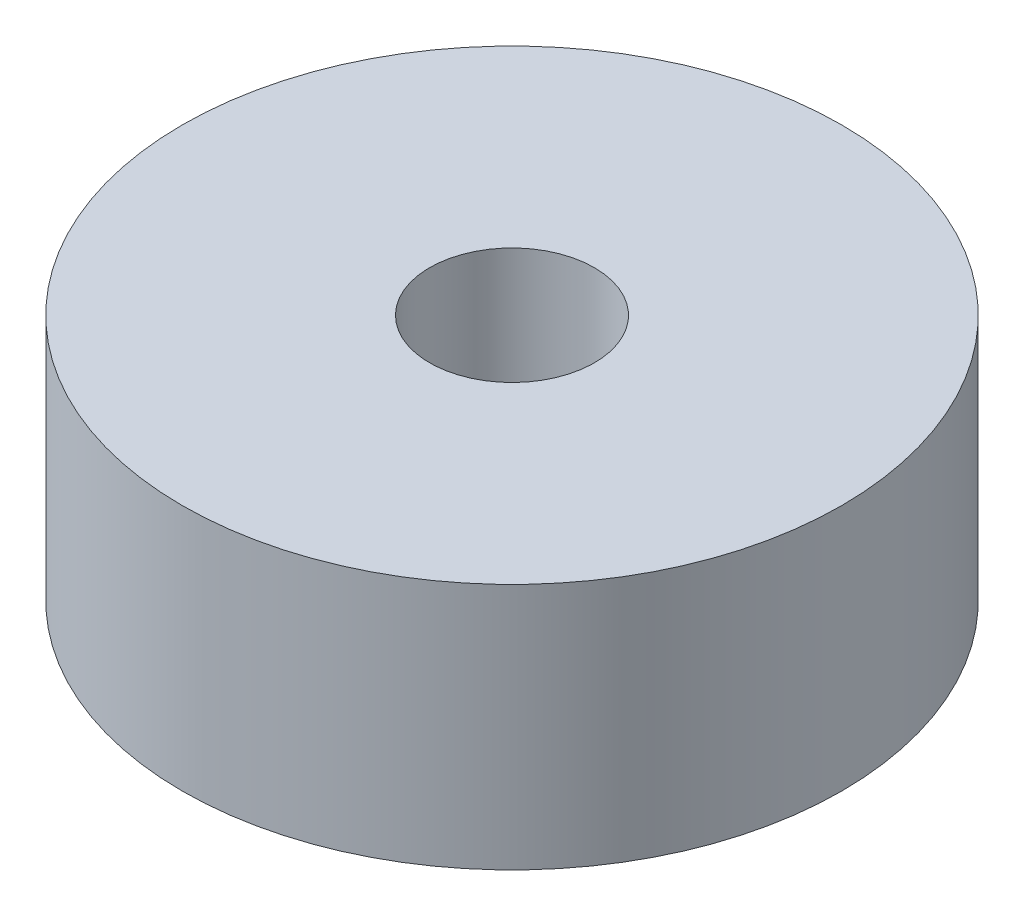
SolidWorks part; units mm, degrees
ref_plane "前视基准面" through (0, 0, 0) normal (0, 0, 1) x (1, 0, 0)
ref_plane "上视基准面" through (0, 0, 0) normal (0, 1, 0) x (1, 0, 0)
ref_plane "右视基准面" through (0, 0, 0) normal (1, 0, 0) x (0, 0, -1)
other "Configuration Table"
sketch "草图1" plane through (0, 0, 0) normal (0, 0, 1) x (1, 0, 0)
  line L0 (0, 0) -> (0, 20) construction
  line L2 (5, 0) -> (15, 0)
  line L3 (5, 0) -> (5, 10)
  line L4 (5, 10) -> (15, 10)
  line L5 (15, 0) -> (15, 10)
revolve "ThinRevolve360" add sketch "草图1" angle 360 about L0
